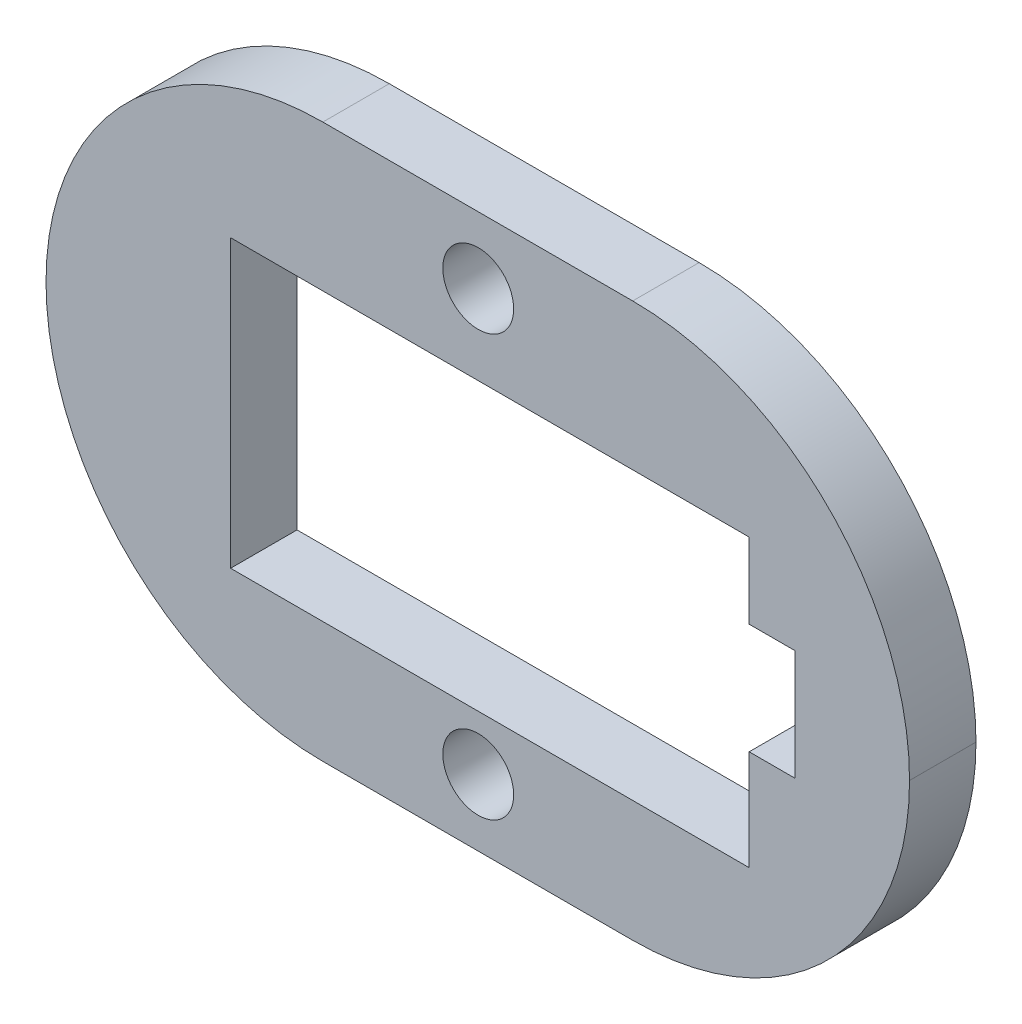
SolidWorks part; units mm, degrees
ref_plane "前视基准面" through (0, 0, 0) normal (0, 0, 1) x (1, 0, 0)
ref_plane "上视基准面" through (0, 0, 0) normal (0, 1, 0) x (1, 0, 0)
ref_plane "右视基准面" through (0, 0, 0) normal (1, 0, 0) x (0, 0, -1)
ref_plane "基准面4" through (0, 0, 0) normal (0, 0, -1) x (-1, 0, 0)
sketch "草图1" plane through (0, 0, 0) normal (0, 0, -1) x (-1, 0, 0)
  line L0 (-12.8054, 14.9897) -> (-10.7446, 14.9897)
  line L1 (-10.7446, 14.9897) -> (-10.7446, 18.3961)
  line L2 (-10.7446, 18.3961) -> (12.6687, 18.3961)
  line L3 (12.6687, 18.3961) -> (12.6687, 5.4702)
  line L4 (12.6687, 5.4702) -> (-10.7446, 5.4702)
  line L5 (-10.7446, 5.4702) -> (-10.7446, 10.001)
  line L6 (-10.7446, 10.001) -> (-12.8054, 10.001)
  line L7 (-12.8054, 10.001) -> (-12.8054, 14.9897)
  line L8 (8.5033, 25.001) -> (-5.4866, 25.001)
  line L9 (-17.9866, 12.501) -> (-17.9866, 12.5)
  line L10 (-5.4866, 0) -> (8.5033, 0)
  arc A0 (8.5033, 0) -> (21.0033, 12.5) centre (8.5033, 12.5) ccw
  arc A1 (21.0033, 12.5) -> (8.5033, 25.001) centre (8.5033, 12.501) ccw
  arc A2 (-5.4866, 25.001) -> (-17.9866, 12.501) centre (-5.4866, 12.501) ccw
  arc A3 (-17.9866, 12.5) -> (-5.4866, 0) centre (-5.4866, 12.5) ccw
  circle A4 centre (1.4879, 21.9995) radius 1.3
  circle A5 centre (1.4879, 2.9995) radius 1.3
  dimension "D1" = 19
extrude "凸台-拉伸1" add sketch "草图1" against normal blind 3
sketch "草图2" plane through (0, 0, 3) normal (0, 0, 1) x (1, 0, 0)
  circle A0 centre (-1.4879, 21.9995) radius 1.6
  circle A1 centre (-1.4879, 2.9995) radius 1.6
  dimension "D1" = 3.2
extrude "切除-拉伸1" cut sketch "草图2" against normal through all
chamfer "倒角1" distance 0.3 angle 45 2 edges at (0.1121, 2.9995, 0) (0.1121, 21.9995, 0)
